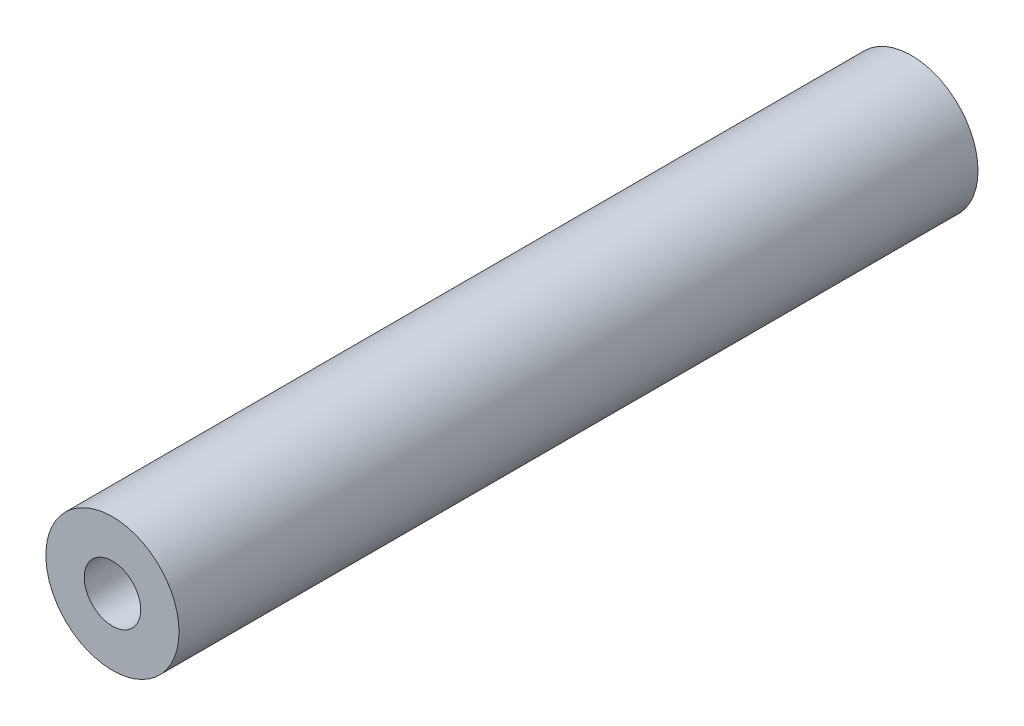
SolidWorks part; units mm, degrees
material "6061-T6 (SS)"
ref_plane "Front Plane" through (0, 0, 0) normal (0, 0, 1) x (1, 0, 0)
ref_plane "Top Plane" through (0, 0, 0) normal (0, 1, 0) x (1, 0, 0)
ref_plane "Right Plane" through (0, 0, 0) normal (1, 0, 0) x (0, 0, -1)
sketch "Sketch1" plane through (0, 0, 0) normal (0, 0, 1) x (1, 0, 0)
  circle A1 centre (0, 0) radius 4.7625
  dimension "D1" = 9.525
extrude "Boss-Extrude1" add sketch "Sketch1" along normal blind 57.15
hole_wizard "#10-32 Tapped Hole1" positions "3DSketch1" profile "Sketch2" tap size "#10-32" standard "ANSI Inch" end condition through all
sketch3d "3DSketch1"
  line L0 (0, 0, 57.15) -> (0, 0, 0) construction
  point P0 (0, 0, 57.15)
  point P4 (0, 0, 0)
sketch "Sketch2" plane through (0, 0, 57.15) normal (1, 0, 0) x (0, -1, 0)
  line L0 (0, 0) -> (0, 57.15)
  line L1 (0, 57.15) -> (2.0193, 57.15)
  line L2 (2.0193, 57.15) -> (2.0193, 0)
  line L5 (2.0193, 0) -> (0, 0)
  line L11 (0, -6.35) -> (0, 107.95) construction
  dimension "Thru Tap Drill Dia." = 4.0386
  dimension "Thru Tap Drill Depth" = 57.15
cosmetic thread "Hole Thread1" parameters "D2"=4.826
cosmetic thread "Hole Thread2" parameters "D2"=4.826
